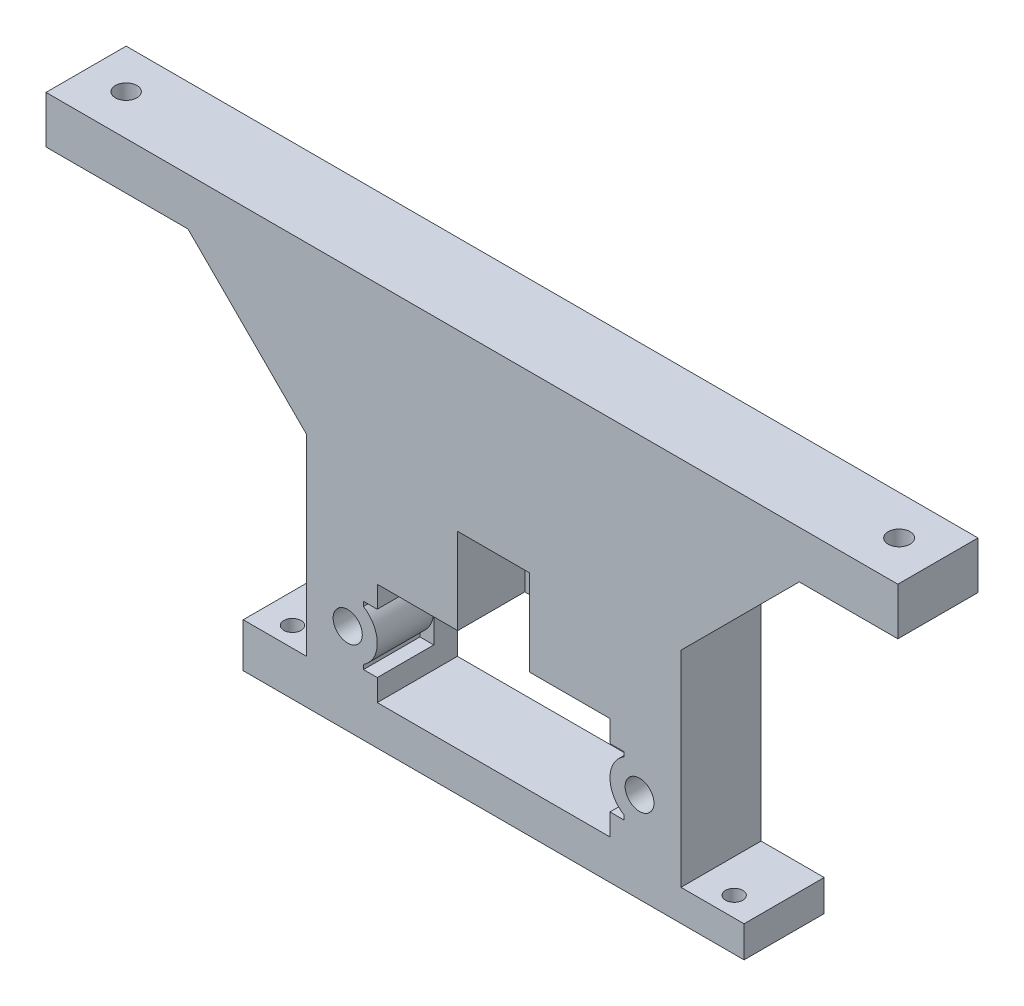
SolidWorks part; units mm, degrees
ref_plane "Front Plane" through (0, 0, 0) normal (0, 0, 1) x (1, 0, 0)
ref_plane "Top Plane" through (0, 0, 0) normal (0, 1, 0) x (1, 0, 0)
ref_plane "Right Plane" through (0, 0, 0) normal (1, 0, 0) x (0, 0, -1)
sketch "Sketch1" plane through (0, 0, 0) normal (0, 1, 0) x (1, 0, 0)
  line L1 (0, 0) -> (63.5, 0)
  line L2 (0, 0) -> (0, 10.16)
  line L3 (0, 10.16) -> (63.5, 10.16)
  line L4 (63.5, 0) -> (63.5, 10.16)
  dimension "D1" = 63.5
  dimension "D2" = 10.16
extrude "Boss-Extrude1" add sketch "Sketch1" along normal blind 51
sketch "Sketch2" plane through (0, 0, 0) normal (0, -1, 0) x (-1, 0, 0)
  circle A0 centre (-59.75, 2.5) radius 1.0922
  circle A1 centre (-3.75, 2.5) radius 1.0922
extrude "Cut-Extrude1" cut sketch "Sketch2" against normal blind 10
sketch "Sketch3" plane through (0, 0, 0) normal (0, 0, 1) x (1, 0, 0)
  line L0 (0, 51) -> (0, 0) construction
  line L1 (0, 5.597) -> (8, 5.597)
  line L2 (0, 5.597) -> (0, 53.307)
  line L3 (0, 53.307) -> (8, 53.307)
  line L4 (8, 5.597) -> (8, 53.307)
  line L5 (63.5, 51) -> (63.5, 0) construction
  line L6 (63.5, 3.9673) -> (55.5, 3.9673)
  line L7 (63.5, 3.9673) -> (63.5, 52.1662)
  line L8 (63.5, 52.1662) -> (55.5, 52.1662)
  line L9 (55.5, 3.9673) -> (55.5, 52.1662)
  dimension "D1" = 8
  dimension "D2" = 8
extrude "Cut-Extrude2" cut sketch "Sketch3" against normal through all both and the other way through all
sketch "Sketch5" plane through (0, 51, 0) normal (0, 1, 0) x (1, 0, 0)
  line L1 (8, 0) -> (-25, 0)
  line L2 (8, 0) -> (8, 10.16)
  line L3 (8, 10.16) -> (-25, 10.16)
  line L4 (-25, 0) -> (-25, 10.16)
  line L5 (55.5, 0) -> (83, 0)
  line L6 (55.5, 0) -> (55.5, 10.16)
  line L7 (55.5, 10.16) -> (83, 10.16)
  line L8 (83, 0) -> (83, 10.16)
  circle A0 centre (-20, 5.16) radius 1.3633
  circle A1 centre (78, 5.16) radius 1.3861
  dimension "D1" = 27.5
  dimension "D2" = 33
  dimension "D3" = 5
  dimension "D4" = 5
  dimension "D5" = 5
  dimension "D6" = 5
extrude "Boss-Extrude2" add sketch "Sketch5" against normal blind 6
chamfer "Chamfer2" distance 15 angle 45 2 edges at (55.5, 45, -5.08) (8, 45, -5.08)
sketch "Sketch6" plane through (0, 0, 0) normal (0, 0, 1) x (1, 0, 0)
  line L0 (36.3, 23.9) -> (27.2, 23.9) construction
  line L1 (17, 18) -> (46.5, 18)
  line L2 (17, 18) -> (17, 5)
  line L3 (17, 5) -> (46.5, 5)
  line L4 (46.5, 18) -> (46.5, 5)
  line L5 (17, 15.25) -> (15.25, 15.25)
  line L6 (17, 15.25) -> (17, 7.75)
  line L7 (17, 7.75) -> (15.25, 7.75)
  line L8 (15.25, 15.25) -> (15.25, 7.75)
  line L9 (46.5, 15.25) -> (48.25, 15.25)
  line L10 (46.5, 15.25) -> (46.5, 7.75)
  line L11 (46.5, 7.75) -> (48.25, 7.75)
  line L12 (48.25, 15.25) -> (48.25, 7.75)
  line L13 (27.2, 18) -> (36.3, 18)
  line L14 (27.2, 18) -> (27.2, 28.9)
  line L15 (27.2, 28.9) -> (36.3, 28.9)
  line L16 (36.3, 18) -> (36.3, 28.9)
  circle A0 centre (13.25, 11.5) radius 1.8495
  circle A1 centre (13.25, 11.5) radius 3.75
  circle A2 centre (50.25, 11.5) radius 1.8292
  circle A3 centre (50.25, 11.5) radius 3.75
  dimension "D1" = 5
extrude "Cut-Extrude3" cut sketch "Sketch6" against normal through all both and the other way through all contours L1 L16 L15 L14 | L4 L1 L2 L6 L3 L10 | A1 L2 L5 L8 | A1 L8 L7 L6 | A0 | A2 | A3 L12 L9 L4 | A3 L10 L11 L12
sketch "Sketch7" plane through (0, 0, -10.16) normal (0, 0, -1) x (-1, 0, 0)
  line L1 (-36.3, 28.9) -> (-27.2, 28.9)
  line L2 (-36.3, 28.9) -> (-36.3, 18)
  line L3 (-36.3, 18) -> (-27.2, 18)
  line L4 (-27.2, 28.9) -> (-27.2, 18)
extrude "Boss-Extrude3" add sketch "Sketch7" against normal up to surface (1.66 mm away)
sketch "Sketch8" plane through (0, 0, -10.16) normal (0, 0, -1) x (-1, 0, 0)
  line L1 (-46.5, 15.25) -> (-48.25, 15.25)
  line L2 (-46.5, 15.25) -> (-46.5, 7.75)
  line L3 (-46.5, 7.75) -> (-48.25, 7.75)
  line L4 (-48.25, 15.25) -> (-48.25, 7.75)
  line L5 (-15.25, 15.25) -> (-17, 15.25)
  line L6 (-15.25, 15.25) -> (-15.25, 7.75)
  line L7 (-15.25, 7.75) -> (-17, 7.75)
  line L8 (-17, 15.25) -> (-17, 7.75)
extrude "Boss-Extrude4" add sketch "Sketch8" against normal blind 3
